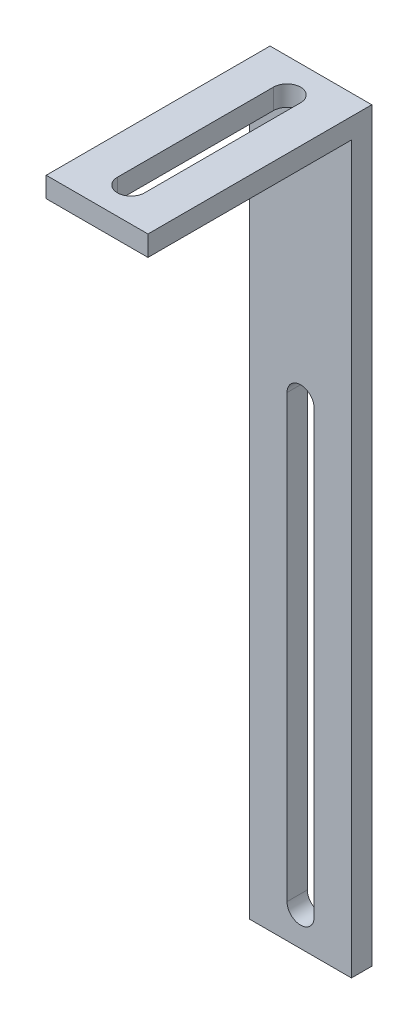
SolidWorks part; units mm, degrees
ref_plane "Front Plane" through (0, 0, 0) normal (0, 0, 1) x (1, 0, 0)
ref_plane "Top Plane" through (0, 0, 0) normal (0, 1, 0) x (1, 0, 0)
ref_plane "Right Plane" through (0, 0, 0) normal (1, 0, 0) x (0, 0, -1)
sketch "Sketch1" plane through (0, 0, 0) normal (0, 0, 1) x (1, 0, 0)
  line L1 (-7.5, 55) -> (7.5, 55)
  line L2 (-7.5, 55) -> (-7.5, -55)
  line L3 (-7.5, -55) -> (7.5, -55)
  line L4 (7.5, 55) -> (7.5, -55)
  line L5 (-7.5, 55) -> (7.5, -55) construction
  line L6 (-7.5, -55) -> (7.5, 55) construction
  point P0 (0, 0)
  dimension "D1" = 110
  dimension "D2" = 15
extrude "Boss-Extrude1" add sketch "Sketch1" along normal blind 3
sketch "Sketch2" plane through (0, 0, 3) normal (0, 0, 1) x (1, 0, 0)
  line L0 (0, 15) -> (0, -50) construction
  line L1 (2, 15) -> (2, -50)
  line L2 (-2, 15) -> (-2, -50)
  line L3 (7.5, 55) -> (-7.5, 55) construction
  line L4 (-7.5, -55) -> (7.5, -55) construction
  arc A0 (2, 15) -> (-2, 15) centre (0, 15) ccw
  arc A1 (-2, -50) -> (2, -50) centre (0, -50) ccw
  point P3 (0, -17.5)
  dimension "D1" = 2
  dimension "D2" = 40
  dimension "D3" = 5
extrude "Cut-Extrude1" cut sketch "Sketch2" against normal blind 3
sketch "Sketch3" plane through (0, 0, 3) normal (0, 0, 1) x (1, 0, 0)
  line L0 (7.5, -55) -> (7.5, 55) construction
  line L1 (-7.5, 55) -> (7.5, 55)
  line L2 (-7.5, 55) -> (-7.5, 52)
  line L3 (-7.5, 52) -> (7.5, 52)
  line L4 (7.5, 55) -> (7.5, 52)
  dimension "D1" = 3
extrude "Boss-Extrude2" add sketch "Sketch3" along normal blind 30
sketch "Sketch4" plane through (0, 55, 0) normal (0, 1, 0) x (1, 0, 0)
  line L0 (0, -5) -> (0, -28) construction
  line L1 (2, -5) -> (2, -28)
  line L2 (-2, -5) -> (-2, -28)
  line L3 (7.5, -33) -> (7.5, 0) construction
  line L4 (7.5, -33) -> (-7.5, -33) construction
  arc A0 (2, -5) -> (-2, -5) centre (0, -5) ccw
  arc A1 (-2, -28) -> (2, -28) centre (0, -28) ccw
  point P2 (0, -16.5)
  dimension "D1" = 2
  dimension "D2" = 7.5
  dimension "D3" = 5
  dimension "D4" = 5
extrude "Cut-Extrude2" cut sketch "Sketch4" against normal blind 30
